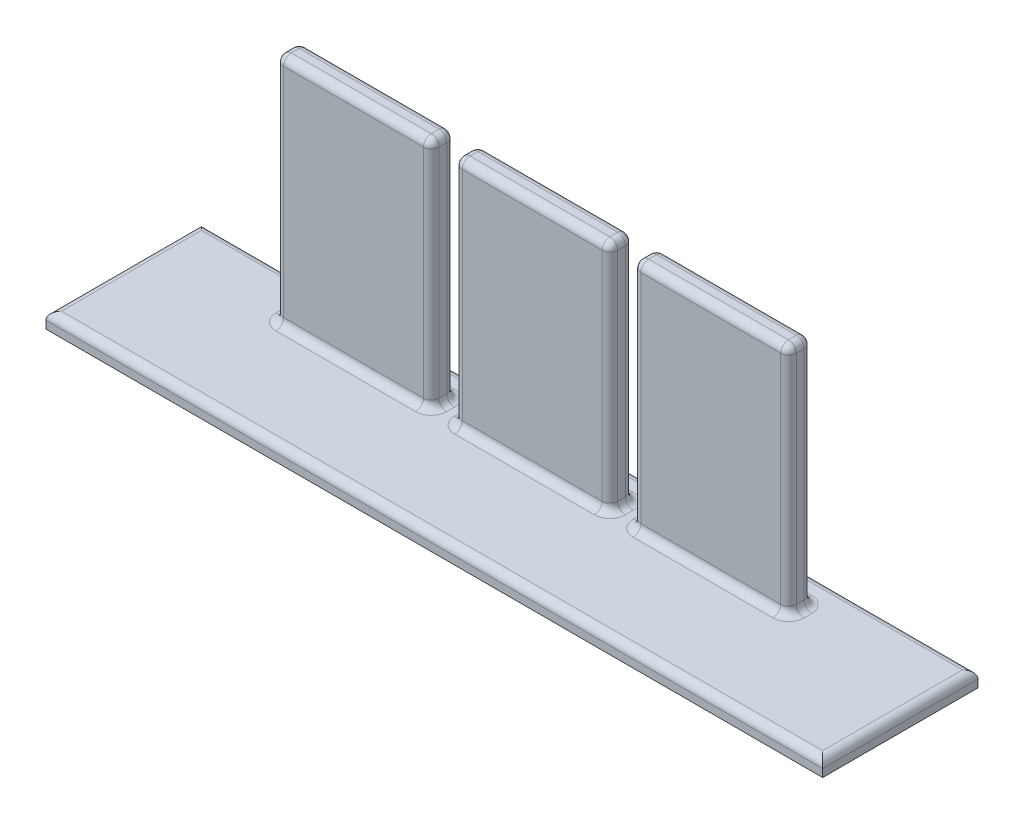
SolidWorks part; units mm, degrees
ref_plane "前视基准面" through (0, 0, 0) normal (0, 0, 1) x (1, 0, 0)
ref_plane "上视基准面" through (0, 0, 0) normal (0, 1, 0) x (1, 0, 0)
ref_plane "右视基准面" through (0, 0, 0) normal (1, 0, 0) x (0, 0, -1)
sketch "草图1" plane through (0, 0, 0) normal (0, 0, 1) x (1, 0, 0)
  line L1 (0, 0) -> (50, 0)
  line L2 (0, 0) -> (0, 1)
  line L3 (0, 1) -> (50, 1)
  line L4 (50, 0) -> (50, 1)
  dimension "D1" = 50
  dimension "D2" = 1
extrude "凸台-拉伸1" add sketch "草图1" along normal blind 10
sketch "草图2" plane through (0, 1, 0) normal (0, 1, 0) x (1, 0, 0)
  line L0 (0, -10) -> (0, 0) construction
  line L1 (8, -1.7) -> (18, -1.7)
  line L2 (8, -1.7) -> (8, -3.2)
  line L3 (8, -3.2) -> (18, -3.2)
  line L4 (18, -1.7) -> (18, -3.2)
  line L5 (19.5, -1.7) -> (29.5, -1.7)
  line L6 (19.5, -1.7) -> (19.5, -3.2)
  line L7 (19.5, -3.2) -> (29.5, -3.2)
  line L8 (29.5, -1.7) -> (29.5, -3.2)
  line L9 (31, -1.7) -> (41, -1.7)
  line L10 (31, -1.7) -> (31, -3.2)
  line L11 (31, -3.2) -> (41, -3.2)
  line L12 (41, -1.7) -> (41, -3.2)
  line L14 (50, 0) -> (0, 0) construction
  dimension "D1" = 10
  dimension "D2" = 10
  dimension "D3" = 10
  dimension "D4" = 8
  dimension "D5" = 1.5
  dimension "D6" = 1.5
  dimension "D7" = 1.7
  dimension "D8" = 1.5
  dimension "D9" = 1.5
  dimension "D10" = 1.5
extrude "凸台-拉伸2" add sketch "草图2" along normal blind 15
fillet "圆角3" radius 0.5 40 edges at (13, 16, 1.7) (50, 1, 5) (25, 1, 10) (0, 1, 5) (25, 1, 0) (13, 1, 1.7) (8, 8.5, 1.7) (8, 16, 2.45) (8, 1, 2.45) (19.5, 1, 2.45) (19.5, 8.5, 1.7) (24.5, 1, 1.7) (31, 1, 2.45) (31, 8.5, 1.7) (36, 1, 1.7) (18, 16, 2.45) (18, 8.5, 1.7) (18, 1, 2.45) (29.5, 8.5, 1.7) (29.5, 1, 2.45) (41, 8.5, 1.7) (41, 1, 2.45) (24.5, 16, 1.7) (29.5, 16, 2.45) (19.5, 16, 2.45) (36, 16, 1.7) (41, 16, 2.45) (31, 16, 2.45) (31, 8.5, 3.2) (36, 16, 3.2) (41, 8.5, 3.2) (36, 1, 3.2) (19.5, 8.5, 3.2) (24.5, 16, 3.2) (29.5, 8.5, 3.2) (24.5, 1, 3.2) (8, 8.5, 3.2) (13, 16, 3.2) (18, 8.5, 3.2) (13, 1, 3.2)
